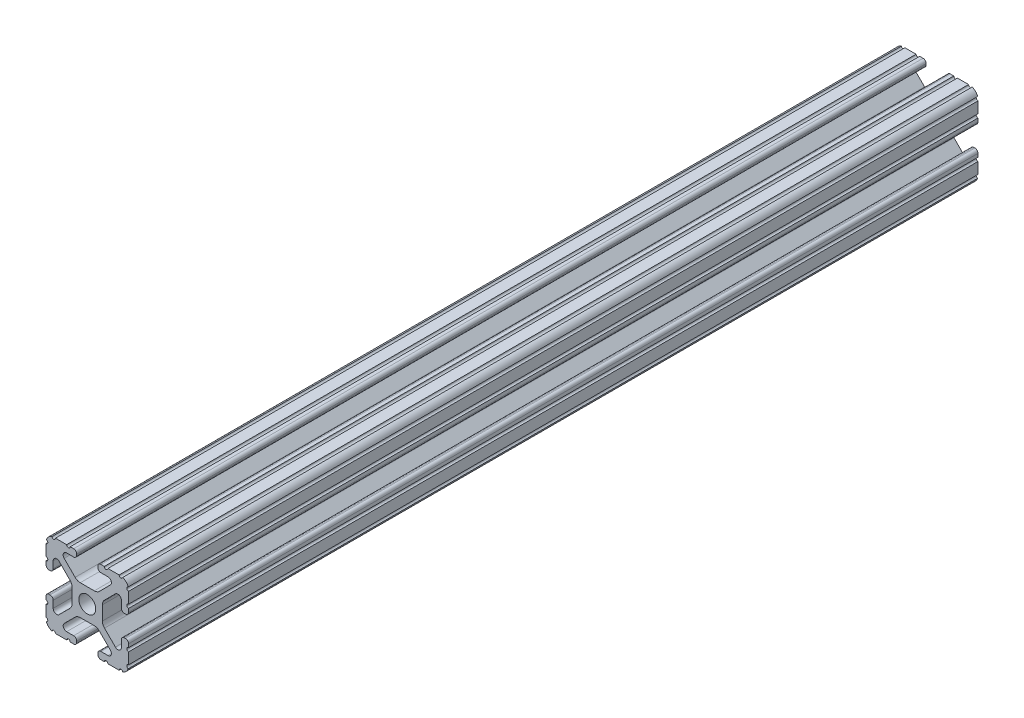
SolidWorks part; units mm, degrees
ref_plane "Front Plane" through (0, 0, 0) normal (0, 0, 1) x (1, 0, 0)
ref_plane "Top Plane" through (0, 0, 0) normal (0, 1, 0) x (1, 0, 0)
ref_plane "Right Plane" through (0, 0, 0) normal (1, 0, 0) x (0, 0, -1)
sketch "Sketch2" plane through (0, 0, 0) normal (0, 0, 1) x (1, 0, 0)
  line L0 (0, 12.7) -> (0, -12.7) construction
  line L1 (-12.7, 0) -> (12.7, 0) construction
  line L2 (3.2512, -12.7) -> (12.7, -12.7)
  line L3 (12.7, -12.7) -> (12.7, -3.2512)
  line L4 (3.2512, -12.7) -> (3.2512, -10.4902)
  line L5 (3.2512, -10.4902) -> (8.9276, -10.4902)
  line L6 (8.9276, -10.4902) -> (3.0856, -4.6482)
  line L7 (0, 0) -> (12.7, -12.7) construction
  line L8 (12.7, -3.2512) -> (10.4902, -3.2512)
  line L9 (10.4902, -3.2512) -> (10.4902, -8.9276)
  line L10 (10.4902, -8.9276) -> (4.6482, -3.0856)
  circle A0 centre (0, 0) radius 2.6035
  arc A1 (6.3485, -10.4902) -> (7.1039, -8.6665) centre (6.3485, -9.4219) ccw construction
  point P8 (0, -4.6482)
  dimension "Center Hole Diameter" = 5.207
  dimension "Rail Height" = 25.4
  dimension "Rail Width" = 25.4
  dimension "T-Slot Width" = 6.5024
  dimension "Slot Inner Width" = 14.8336
  dimension "Thickness" = 2.2098
  dimension "Slot Depth" = 5.842
  dimension "D1" = 2.2098
sketch "Sketch3" plane through (0, 0, 0) normal (1, 0, 0) x (0, 0, -1)
  line L0 (-130.6889, -12.7) -> (130.6889, -12.7) construction
  line L1 (-105.2889, 0) -> (105.2889, 0) construction
  line L3 (130.6889, 0) -> (-130.6889, 0) construction
sketch "Sketch4" plane through (0, 0, 0) normal (0, 0, 1) x (1, 0, 0)
  line L0 (4.1904, -12.7) -> (10.1173, -12.7)
  line L1 (3.2512, -12.7) -> (12.7, -12.7) construction
  line L2 (3.2512, -12.7) -> (3.2512, -10.4902) construction
  line L3 (3.2512, -10.4902) -> (8.9276, -10.4902) construction
  line L4 (3.2512, -11.4294) -> (3.2512, -11.7608)
  line L5 (4.1904, -10.4902) -> (6.3485, -10.4902)
  line L6 (0, -4.6482) -> (2.164, -4.6482)
  line L7 (8.9276, -10.4902) -> (3.0856, -4.6482) construction
  line L8 (3.7373, -5.2999) -> (7.1039, -8.6665)
  line L9 (12.7, -12.7) -> (12.7, -3.2512) construction
  line L10 (10.4902, -8.9276) -> (4.6482, -3.0856) construction
  line L11 (10.4902, -3.2512) -> (10.4902, -8.9276) construction
  line L12 (10.4902, -6.3485) -> (10.4902, -4.1904)
  line L13 (12.7, -3.2512) -> (10.4902, -3.2512) construction
  line L14 (11.4294, -3.2512) -> (11.7608, -3.2512)
  line L15 (12.7, -4.1904) -> (12.7, -10.1173)
  line L16 (8.6665, -7.1039) -> (5.2999, -3.7373)
  line L17 (4.6482, 0) -> (4.6482, -2.164)
  line L18 (-12.7, 0) -> (12.7, 0) construction
  line L19 (0, -4.6482) -> (0, -2.6035)
  line L20 (0, 12.7) -> (0, -12.7) construction
  line L21 (4.6482, 0) -> (2.6035, 0)
  arc A0 (3.2512, -11.7608) -> (4.1904, -12.7) centre (4.1904, -11.7608) ccw
  arc A2 (3.2512, -11.4294) -> (4.1904, -10.4902) centre (4.1904, -11.4294) cw
  arc A3 (6.3485, -10.4902) -> (7.1039, -8.6665) centre (6.3485, -9.4219) ccw
  arc A4 (2.164, -4.6482) -> (3.7373, -5.2999) centre (2.164, -6.8732) cw
  arc A5 (10.1173, -12.7) -> (12.7, -10.1173) centre (10.1173, -10.1173) ccw
  arc A6 (8.6665, -7.1039) -> (10.4902, -6.3485) centre (9.4219, -6.3485) ccw
  arc A7 (10.4902, -4.1904) -> (11.4294, -3.2512) centre (11.4294, -4.1904) cw
  arc A8 (11.7608, -3.2512) -> (12.7, -4.1904) centre (11.7608, -4.1904) cw
  arc A9 (5.2999, -3.7373) -> (4.6482, -2.164) centre (6.8732, -2.164) cw
  circle A10 centre (0, 0) radius 2.6035 construction
  arc A11 (0, -2.6035) -> (2.6035, 0) centre (0, 0) ccw
  dimension "D1" = 2.5827
  dimension "D2" = 2.225
  dimension "D3" = 0.9392
extrude "Boss-Extrude1" add sketch "Sketch4" along normal up to vertex (130.6889 mm away) from vertex at -130.6889 starting at point (0, -12.7, -130.6889)
sketch "Sketch5" plane through (0, 0, 0) normal (0, 0, 1) x (1, 0, 0)
  line L0 (3.2512, -12.7) -> (12.7, -12.7) construction
  line L1 (4.1904, -10.4902) -> (6.3485, -10.4902) construction
  line L3 (0, 0) -> (12.7, -12.7) construction
  line L4 (6.3485, -10.4902) -> (6.3485, -12.7) construction
  line L5 (8.9276, -10.4902) -> (3.0856, -4.6482) construction
  circle A0 centre (10.3562, -12.7) radius 0.5524
  circle A1 centre (5.796, -12.7) radius 0.5524
  circle A2 centre (12.7, -10.3562) radius 0.5524
  circle A3 centre (12.7, -5.796) radius 0.5524
  point P10 (5.2694, -10.4902)
  point P12 (9.4219, -6.3485)
  dimension "D1" = 1.1049
extrude "Cut-Extrude1" cut sketch "Sketch5" against normal through all both and the other way through all
mirror "Mirror1" about plane through (0, 0, 0) normal (1, 0, 0) of bodies 137 134
mirror "Mirror2" about plane through (0, 0, 0) normal (0, 1, 0) of bodies 135
equation "\"D1@Sketch2\"=\"Thickness@Sketch2\""
equation "\"D2@Sketch4\"=\"Slot Inner Width@Sketch2\"*0.15"
equation "\"D1@Sketch4\"=\"D3@Sketch4\"*2.75"
equation "\"D3@Sketch4\"=\"Thickness@Sketch2\"*0.425"
equation "\"D1@Sketch5\"=\"Thickness@Sketch2\"*0.5"
equation "\"D1@Boss-Extrude1\"=\"Length@Sketch3\""
